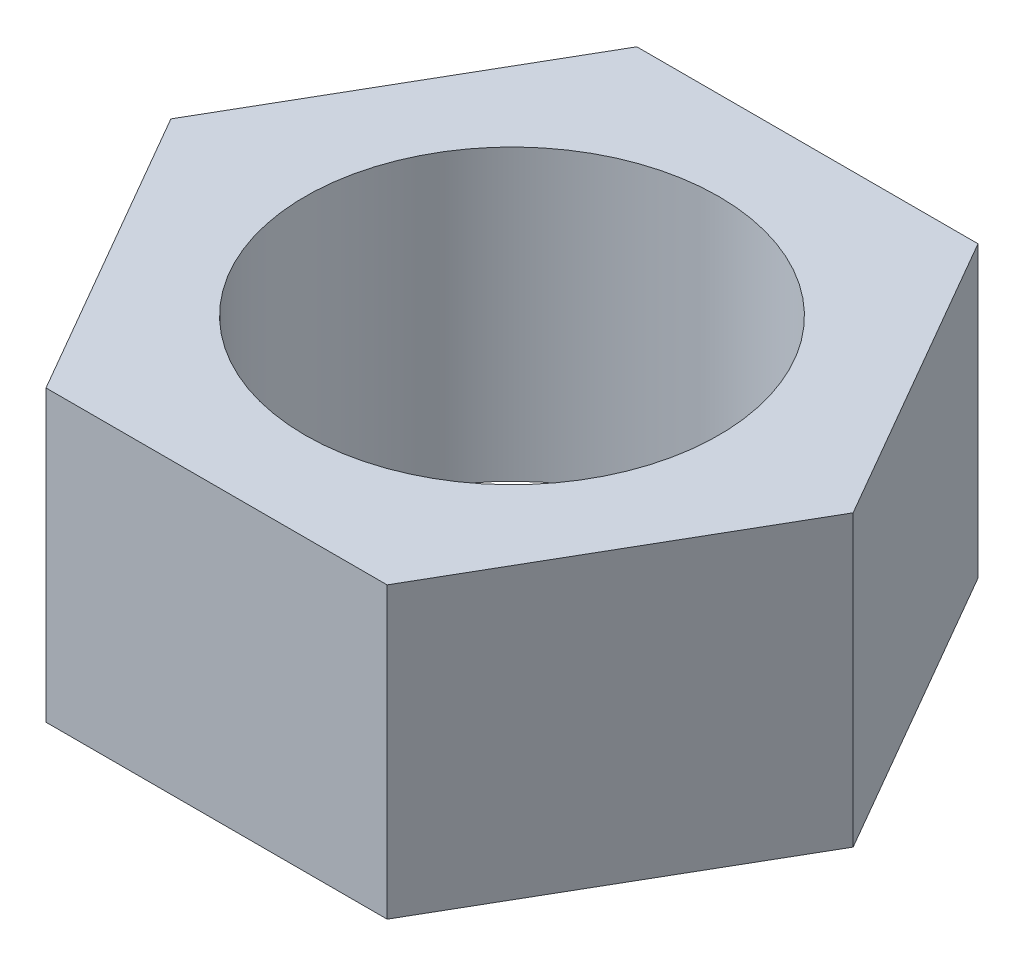
SolidWorks part; units mm, degrees
material "Nylon 6/10"
ref_plane "Front Plane" through (0, 0, 0) normal (0, 0, 1) x (1, 0, 0)
ref_plane "Top Plane" through (0, 0, 0) normal (0, 1, 0) x (1, 0, 0)
ref_plane "Right Plane" through (0, 0, 0) normal (1, 0, 0) x (0, 0, -1)
sketch "Sketch1" plane through (0, 0, 0) normal (0, 1, 0) x (1, 0, 0)
  line L1 (1.4665, 2.54) -> (-1.4665, 2.54)
  line L2 (-1.4665, 2.54) -> (-2.9329, 0)
  line L3 (-2.9329, 0) -> (-1.4665, -2.54)
  line L4 (-1.4665, -2.54) -> (1.4665, -2.54)
  line L5 (1.4665, -2.54) -> (2.9329, 0)
  line L6 (2.9329, 0) -> (1.4665, 2.54)
  circle A0 centre (0, 0) radius 2.54 construction
  dimension "D1" = 5.08
extrude "Boss-Extrude1" add sketch "Sketch1" along normal blind 2.4892
sketch "Sketch2" plane through (0, 2.4892, 0) normal (0, 1, 0) x (1, 0, 0)
  circle A0 centre (0, 0) radius 1.778
  dimension "D1" = 3.556
extrude "Cut-Extrude1" cut sketch "Sketch2" against normal through all
